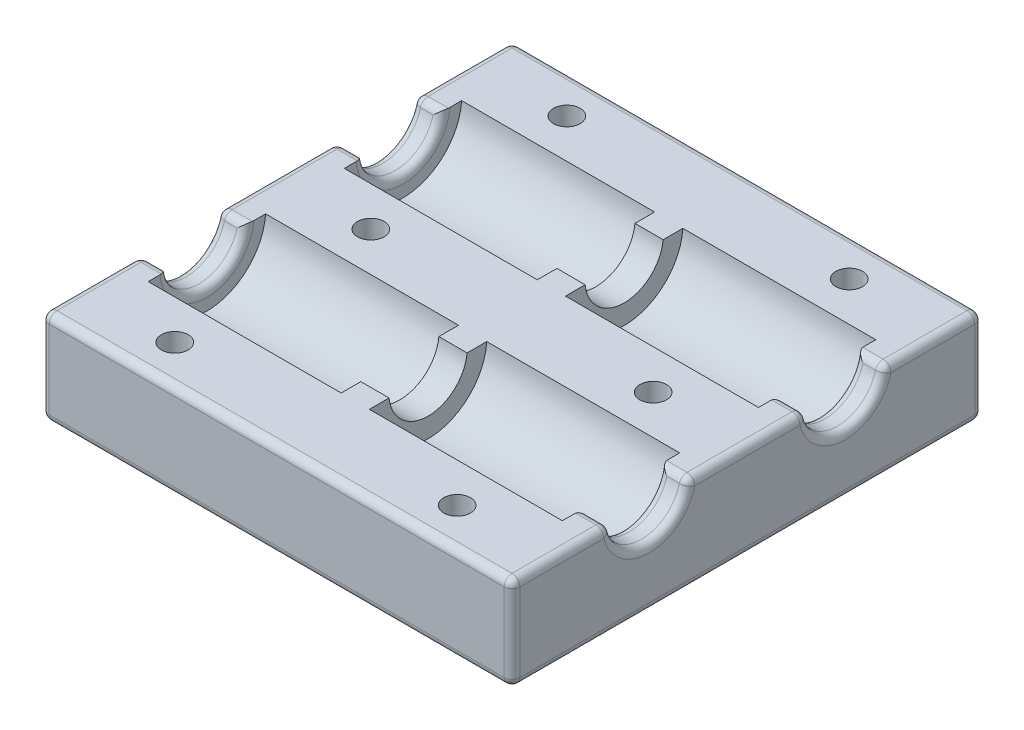
SolidWorks part; units mm, degrees
ref_plane "Front Plane" through (0, 0, 0) normal (0, 0, 1) x (1, 0, 0)
ref_plane "Top Plane" through (0, 0, 0) normal (0, 1, 0) x (1, 0, 0)
ref_plane "Right Plane" through (0, 0, 0) normal (1, 0, 0) x (0, 0, -1)
sketch "Sketch1" plane through (0, 0, 0) normal (0, 1, 0) x (1, 0, 0)
  line L1 (-30, -30) -> (30, -30)
  line L2 (-30, -30) -> (-30, 30)
  line L3 (-30, 30) -> (30, 30)
  line L4 (30, -30) -> (30, 30)
  line L5 (-30, -30) -> (30, 30) construction
  line L6 (-30, 30) -> (30, -30) construction
  point P0 (0, 0)
  dimension "D1" = 60
  dimension "D2" = 60
extrude "Boss-Extrude1" add sketch "Sketch1" along normal blind 25
sketch "Sketch2" plane through (30, 0, 0) normal (1, 0, 0) x (0, 0, -1)
  line L0 (0, 0) -> (0, 25) construction
  line L1 (-30, 25) -> (30, 25) construction
  line L2 (-30, 12.5) -> (-12.5, 12.5) construction
  line L3 (-30, 25) -> (-30, 0) construction
  line L4 (-12.5, 12.5) -> (12.5, 12.5) construction
  line L5 (12.5, 12.5) -> (30, 12.5) construction
  line L6 (30, 25) -> (30, 0) construction
  circle A0 centre (-12.5, 12.5) radius 7.5
  circle A1 centre (12.5, 12.5) radius 7.5
  point P15 (0, 12.5)
  dimension "D2" = 15
  dimension "D1" = 25
extrude "Cut-Extrude1" cut sketch "Sketch2" against normal up to next
sketch "Sketch3" plane through (0, 25, 0) normal (0, 1, 0) x (1, 0, 0)
  line L0 (0, 30) -> (0, -30) construction
  line L1 (30, 30) -> (-30, 30) construction
  line L2 (-30, -30) -> (30, -30) construction
  line L3 (-30, 30) -> (-30, -30) construction
  line L4 (-25, -25) -> (25, -25) construction
  line L5 (-25, -25) -> (-25, 25) construction
  line L6 (-25, 25) -> (25, 25) construction
  line L7 (25, -25) -> (25, 25) construction
  line L8 (-25, -25) -> (25, 25) construction
  line L9 (-25, 25) -> (25, -25) construction
  circle A0 centre (0, 25) radius 2
  circle A1 centre (0, -25) radius 2
  circle A2 centre (-25, 25) radius 2
  circle A3 centre (-25, -25) radius 2
  circle A4 centre (25, -25) radius 2
  circle A5 centre (25, 25) radius 2
  point P10 (0, 0)
  dimension "D3" = 4
  dimension "D1" = 5
  dimension "D2" = 5
  dimension "D4" = 50
  dimension "D5" = 5
extrude "Cut-Extrude2" cut sketch "Sketch3" against normal blind 5
sketch "Sketch7" plane through (0, 0, 0) normal (1, 0, 0) x (0, 0, -1)
  circle A2 centre (12.5, 12.5) radius 7.5 construction
  circle A3 centre (-12.5, 12.5) radius 7.5 construction
  circle A4 centre (12.5, 12.5) radius 7.5
  circle A5 centre (-12.5, 12.5) radius 7.5
extrude "Boss-Extrude2" add sketch "Sketch7" along normal mid plane 3.6
sketch "Sketch8" plane through (30, 0, 0) normal (1, 0, 0) x (0, 0, -1)
  circle A0 centre (12.5, 12.5) radius 7.5 construction
  circle A1 centre (-12.5, 12.5) radius 7.5 construction
  circle A2 centre (12.5, 12.5) radius 7.5
  circle A3 centre (-12.5, 12.5) radius 7.5
  circle A4 centre (-12.5, 12.5) radius 5
  circle A5 centre (12.5, 12.5) radius 5
  dimension "D1" = 10
  dimension "D2" = 10
extrude "Boss-Extrude3" add sketch "Sketch8" against normal blind 3.6
mirror "Mirror1" about plane through (0, 0, 0) normal (1, 0, 0) of "Boss-Extrude3"
sketch "Sketch4" plane through (30, 0, 0) normal (1, 0, 0) x (0, 0, -1)
  line L0 (-30, 12.5) -> (30, 12.5) construction
  line L1 (-30, 25) -> (-30, 0) construction
  line L2 (30, 25) -> (30, 0) construction
  line L4 (-30, 12) -> (30, 12)
  line L5 (-30, 12) -> (-30, 13)
  line L6 (-30, 13) -> (30, 13)
  line L7 (30, 12) -> (30, 13)
  line L8 (-30, 12) -> (30, 13) construction
  line L9 (-30, 13) -> (30, 12) construction
  point P6 (0, 12.5)
  dimension "D1" = 1
extrude "Cut-Extrude3" cut sketch "Sketch4" against normal through all
sketch "Sketch5" plane through (0, 12, 0) normal (0, 1, 0) x (1, 0, 0)
  line L0 (-30, 24.9917) -> (-18, 24.9917) construction
  line L1 (-30, -7.5251) -> (-30, 7.5251) construction
  line L2 (30, -7.5251) -> (30, 7.5251) construction
  line L3 (14.1, -19.9833) -> (14.1, -30) construction
  line L4 (1.8, -19.9833) -> (26.4, -19.9833) construction
  line L5 (-30, -30) -> (30, -30) construction
  line L6 (30, -30) -> (30, -17.4749) construction
  line L7 (-30, -24.9917) -> (-18, -24.9917) construction
  line L9 (-18, -24.9917) -> (18, -24.9917) construction
  line L10 (18, -24.9917) -> (30, -24.9917) construction
  line L13 (-18, 24.9917) -> (18, 24.9917) construction
  line L14 (18, 24.9917) -> (30, 24.9917) construction
  line L16 (-30, 0) -> (-18, 0) construction
  line L18 (-18, 0) -> (18, 0) construction
  line L19 (18, 0) -> (30, 0) construction
  line L21 (-30, -30) -> (-30, -17.4749) construction
  line L22 (14.1, 19.9833) -> (14.1, 30) construction
  line L23 (26.4, 19.9833) -> (1.8, 19.9833) construction
  line L24 (-30, 30) -> (30, 30) construction
  line L25 (-30, 17.4749) -> (-30, 30) construction
  line L26 (30, 17.4749) -> (30, 30) construction
  circle A0 centre (-18, -24.9917) radius 1.7
  circle A1 centre (18, -24.9917) radius 1.7
  circle A2 centre (18, 24.9917) radius 1.7
  circle A3 centre (-18, 24.9917) radius 1.7
  circle A4 centre (18, 0) radius 1.7
  circle A5 centre (-18, 0) radius 1.7
  point P22 (14.1, -24.9917)
  point P29 (14.1, 24.9917)
  dimension "D2" = 3.4
  dimension "D1" = 12
extrude "Cut-Extrude4" cut sketch "Sketch5" against normal through all
fillet "Fillet1" radius 1 32 edges at (0, 0, 30) (0, 12, 30) (30, 0, 0) (30, 6, 30) (30, 12, 23.7375) (30, 12, 0) (30, 12, -23.7375) (0, 0, -30) (30, 6, -30) (0, 12, -30) (-30, 0, 0) (-30, 6, -30) (-30, 12, -23.7375) (-30, 12, 0) (-30, 12, 23.7375) (-30, 6, 30) (-28.2, 12, 17.4749) (-26.4, 7.5, 12.5) (-28.2, 12, 7.5251) (-30, 7.5, 12.5) (-28.2, 12, -7.5251) (-26.4, 7.5, -12.5) (-28.2, 12, -17.4749) (-30, 7.5, -12.5) (28.2, 12, -17.4749) (28.2, 12, -7.5251) (26.4, 7.5, -12.5) (30, 7.5, -12.5) (28.2, 12, 7.5251) (28.2, 12, 17.4749) (26.4, 7.5, 12.5) (30, 7.5, 12.5)
sketch "Sketch9" plane through (30, 0, 0) normal (1, 0, 0) x (0, 0, -1)
  circle A0 centre (-12.5, 12.5) radius 4 construction
  circle A1 centre (12.5, 12.5) radius 4 construction
  circle A2 centre (12.5, 12.5) radius 5
  circle A3 centre (-12.5, 12.5) radius 5
  dimension "D1" = 10
extrude "Cut-Extrude5" cut sketch "Sketch9" against normal through all
